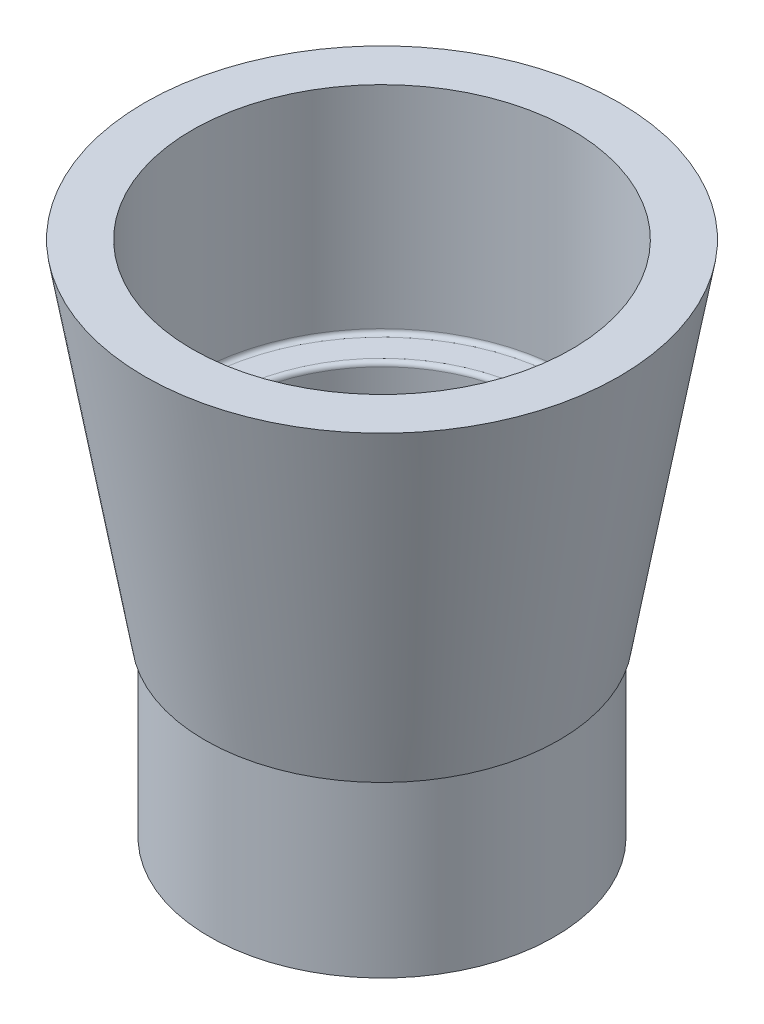
SolidWorks part; units mm, degrees
material "Thornel VCB-20 Carbon Cloth"
ref_plane "Front Plane" through (0, 0, 0) normal (0, 0, 1) x (1, 0, 0)
ref_plane "Top Plane" through (0, 0, 0) normal (0, 1, 0) x (1, 0, 0)
ref_plane "Right Plane" through (0, 0, 0) normal (1, 0, 0) x (0, 0, -1)
sketch "Sketch5" plane through (0, 0, 0) normal (0, 0, 1) x (1, 0, 0)
  line L0 (0, 0) -> (0, 50.8)
  line L1 (0, 50.8) -> (-34.925, 50.8)
  line L2 (-34.925, 50.8) -> (-26.0604, 0)
  line L3 (-26.0604, 0) -> (0, 0)
  dimension "D1" = 50.8
  dimension "D2" = 34.925
  dimension "D3" = 26.0604
revolve "Revolve1" add sketch "Sketch5" angle 360 about L0
sketch "Sketch6" plane through (0, 0, 0) normal (0, -1, 0) x (1, 0, 0)
  circle A0 centre (0, 0) radius 25.4
  dimension "D1" = 50.8
extrude "Boss-Extrude2" add sketch "Sketch6" along normal blind 25.4
sketch "Sketch7" plane through (0, -25.4, 0) normal (0, -1, 0) x (1, 0, 0)
  circle A2 centre (0, 0) radius 22.86
  circle A3 centre (0, 0) radius 22.86
  dimension "D1" = 2.54
extrude "Cut-Extrude1" cut sketch "Sketch7" against normal through all
sketch "Sketch8" plane through (0, 50.8, 0) normal (0, 1, 0) x (1, 0, 0)
  circle A0 centre (0, 0) radius 27.94
  dimension "D1" = 55.88
extrude "Cut-Extrude2" cut sketch "Sketch8" against normal blind 31.75
fillet "Fillet1" radius 0.635 2 edges at (0, 19.05, 22.86) (0, 19.05, 27.94)
